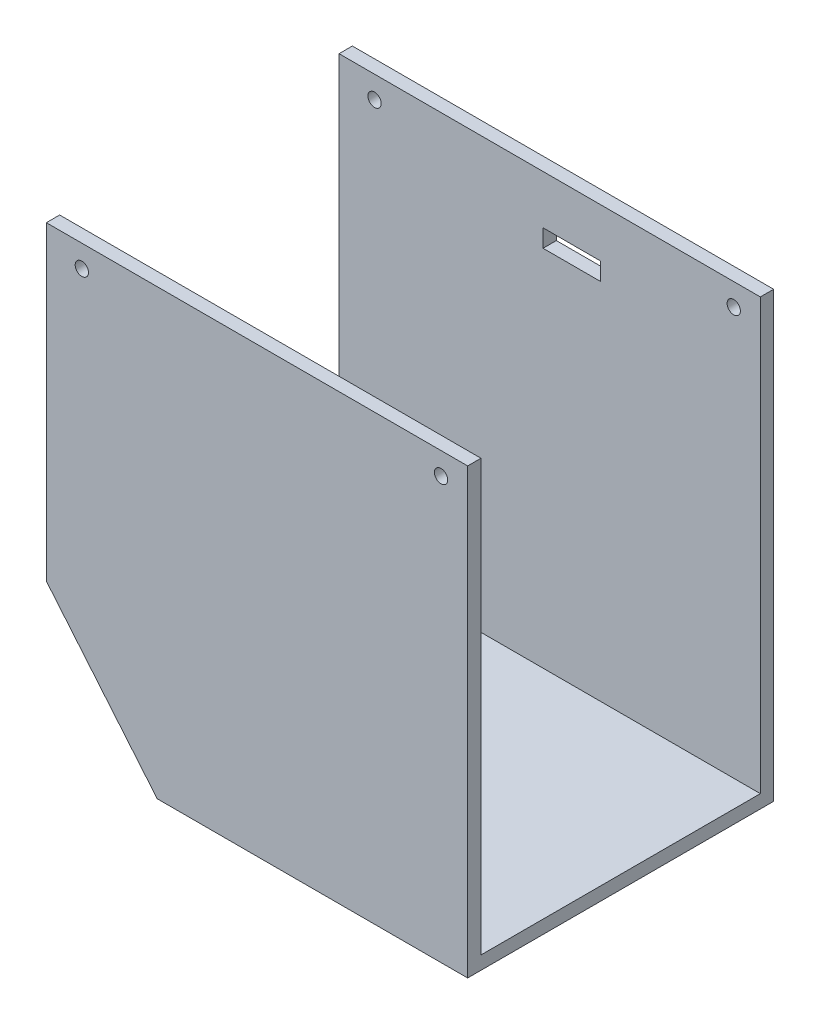
SolidWorks part; units mm, degrees
ref_plane "Front Plane" through (0, 0, 0) normal (0, 0, 1) x (1, 0, 0)
ref_plane "Top Plane" through (0, 0, 0) normal (0, 1, 0) x (1, 0, 0)
ref_plane "Right Plane" through (0, 0, 0) normal (1, 0, 0) x (0, 0, -1)
sketch "Sketch1" plane through (0, 0, 0) normal (0, 1, 0) x (1, 0, 0)
  line L1 (-42.6208, 43.6715) -> (52.3792, 43.6715)
  line L2 (-42.6208, 43.6715) -> (-42.6208, -25.3285)
  line L3 (-42.6208, -25.3285) -> (52.3792, -25.3285)
  line L4 (52.3792, 43.6715) -> (52.3792, -25.3285)
  dimension "D1" = 95
  dimension "D2" = 69
extrude "Boss-Extrude1" add sketch "Sketch1" against normal blind 3
sketch "Sketch2" plane through (0, 0, 0) normal (0, 1, 0) x (1, 0, 0)
  line L0 (-42.6208, 43.6715) -> (-42.6208, -25.3285) construction
  line L1 (-42.6208, -22.3285) -> (52.3792, -22.3285)
  line L2 (-42.6208, -22.3285) -> (-42.6208, -25.3285)
  line L3 (-42.6208, -25.3285) -> (52.3792, -25.3285)
  line L4 (52.3792, -22.3285) -> (52.3792, -25.3285)
  dimension "D1" = 3
extrude "Boss-Extrude2" add sketch "Sketch2" along normal blind 100
sketch "Sketch3" plane through (0, 0, 0) normal (0, 1, 0) x (1, 0, 0)
  line L0 (52.3792, -22.3285) -> (52.3792, 43.6715) construction
  line L1 (-42.6208, 43.6715) -> (52.3792, 43.6715)
  line L2 (-42.6208, 43.6715) -> (-42.6208, 40.6715)
  line L3 (-42.6208, 40.6715) -> (52.3792, 40.6715)
  line L4 (52.3792, 43.6715) -> (52.3792, 40.6715)
  dimension "D1" = 3
extrude "Boss-Extrude3" add sketch "Sketch3" along normal blind 100
sketch "Sketch4" plane through (0, 0, -43.6715) normal (0, 0, -1) x (-1, 0, 0)
  line L5 (42.6208, -3) -> (42.6208, 100) construction
  line L6 (42.6208, 97) -> (-52.3792, 97)
  line L7 (42.6208, 97) -> (42.6208, 100)
  line L8 (42.6208, 100) -> (-52.3792, 100)
  line L9 (-52.3792, 97) -> (-52.3792, 100)
  dimension "D1" = 3
extrude "Cut-Extrude1" cut sketch "Sketch4" against normal blind 100
sketch "Sketch5" plane through (0, 0, -43.6715) normal (0, 0, -1) x (-1, 0, 0)
  line L0 (-52.3792, -3) -> (-52.3792, 97) construction
  line L1 (2.6208, 2) -> (-22.3792, 2)
  line L2 (2.6208, 2) -> (2.6208, 38)
  line L3 (2.6208, 38) -> (-22.3792, 38)
  line L4 (-22.3792, 2) -> (-22.3792, 38)
  line L5 (-52.3792, -3) -> (42.6208, -3) construction
  dimension "D1" = 25
  dimension "D2" = 36
  dimension "D3" = 30
  dimension "D4" = 5
extrude "Cut-Extrude2" cut sketch "Sketch5" against normal blind 1.5 contours L2 L1 L4 L3
sketch "Sketch6" plane through (0, -3, 0) normal (0, -1, 0) x (1, 0, 0)
  line L0 (52.3792, 25.3285) -> (52.3792, -43.6715) construction
  line L1 (-7.6208, -3.6715) -> (22.3792, -3.6715)
  line L2 (-7.6208, -3.6715) -> (-7.6208, -33.6715)
  line L3 (-7.6208, -33.6715) -> (22.3792, -33.6715)
  line L4 (22.3792, -3.6715) -> (22.3792, -33.6715)
  line L5 (52.3792, -43.6715) -> (-42.6208, -43.6715) construction
  dimension "D1" = 30
  dimension "D2" = 30
  dimension "D3" = 30
  dimension "D4" = 10
extrude "Cut-Extrude3" cut sketch "Sketch6" against normal blind 1.5
sketch "Sketch7" plane through (0, 0, -43.6715) normal (0, 0, -1) x (-1, 0, 0)
  line L0 (-52.3792, 97) -> (42.6208, 97) construction
  line L1 (42.6208, -3) -> (42.6208, 97) construction
  circle A0 centre (34.6208, 92) radius 1.5
  circle A1 centre (-46.3792, 92) radius 1.5
  point P4 (0, 0)
  point P7 (0, 0)
  point P10 (-38.5997, 92)
  dimension "D1" = 3
  dimension "D2" = 5
  dimension "D3" = 8
  dimension "D4" = 81
extrude "Cut-Extrude5" cut sketch "Sketch7" against normal through all
sketch "Sketch8" plane through (0, 0, -43.6715) normal (0, 0, -1) x (-1, 0, 0)
  line L0 (42.6208, -3) -> (17.6208, -3)
  line L1 (-52.3792, -3) -> (42.6208, -3) construction
  line L2 (17.6208, -3) -> (42.6208, 27)
  line L3 (42.6208, -3) -> (42.6208, 97) construction
  line L4 (42.6208, 27) -> (42.6208, -3)
  dimension "D1" = 25
  dimension "D2" = 30
extrude "Cut-Extrude6" cut sketch "Sketch8" against normal through all
sketch "Sketch9" plane through (0, 0, -43.6715) normal (0, 0, -1) x (-1, 0, 0)
  line L0 (2.6208, 38) -> (2.6208, 97)
  line L1 (-52.3792, 97) -> (42.6208, 97) construction
  line L2 (-22.3792, 38) -> (-22.3792, 97)
  line L4 (-3.3792, 86) -> (-16.3792, 86)
  line L5 (-3.3792, 86) -> (-3.3792, 82)
  line L6 (-3.3792, 82) -> (-16.3792, 82)
  line L7 (-16.3792, 86) -> (-16.3792, 82)
  dimension "D1" = 13
  dimension "D2" = 6
  dimension "D3" = 15
  dimension "D4" = 4
extrude "Cut-Extrude9" cut sketch "Sketch9" against normal blind 10 contours L4 L7 L6 L5
